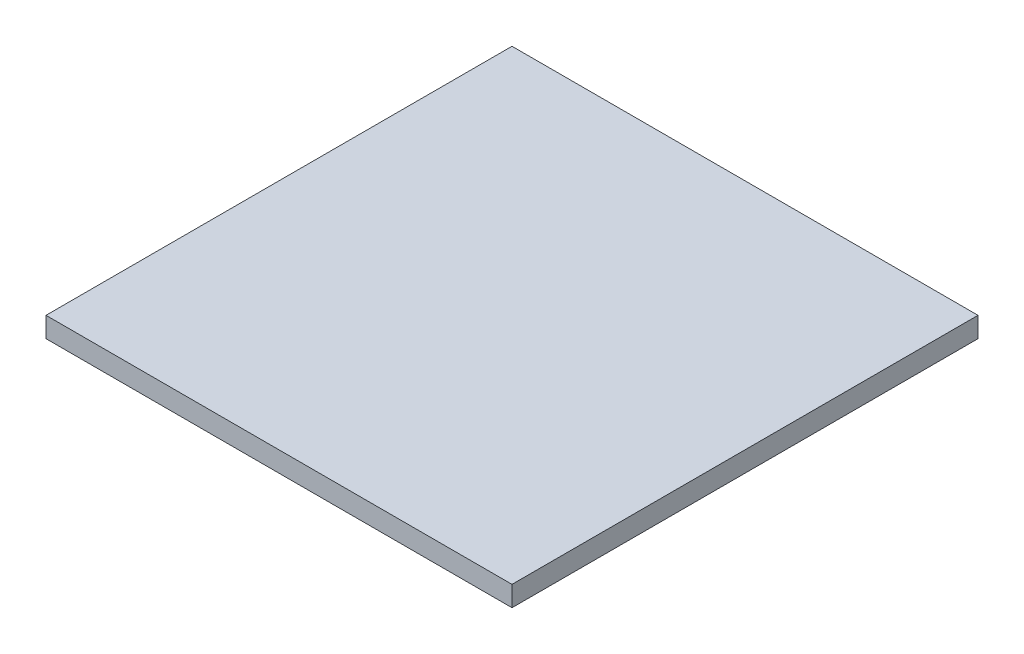
SolidWorks part; units mm, degrees
material "Pine"
ref_plane "Front Plane" through (0, 0, 0) normal (0, 0, 1) x (1, 0, 0)
ref_plane "Top Plane" through (0, 0, 0) normal (0, 1, 0) x (1, 0, 0)
ref_plane "Right Plane" through (0, 0, 0) normal (1, 0, 0) x (0, 0, -1)
sketch "Sketch1" plane through (0, 0, 0) normal (0, 1, 0) x (1, 0, 0)
  line L1 (0, 0) -> (276, 0)
  line L2 (0, 0) -> (0, 276)
  line L3 (0, 276) -> (276, 276)
  line L4 (276, 0) -> (276, 276)
  dimension "D1" = 276
  dimension "D2" = 276
extrude "Boss-Extrude1" add sketch "Sketch1" along normal blind 12
